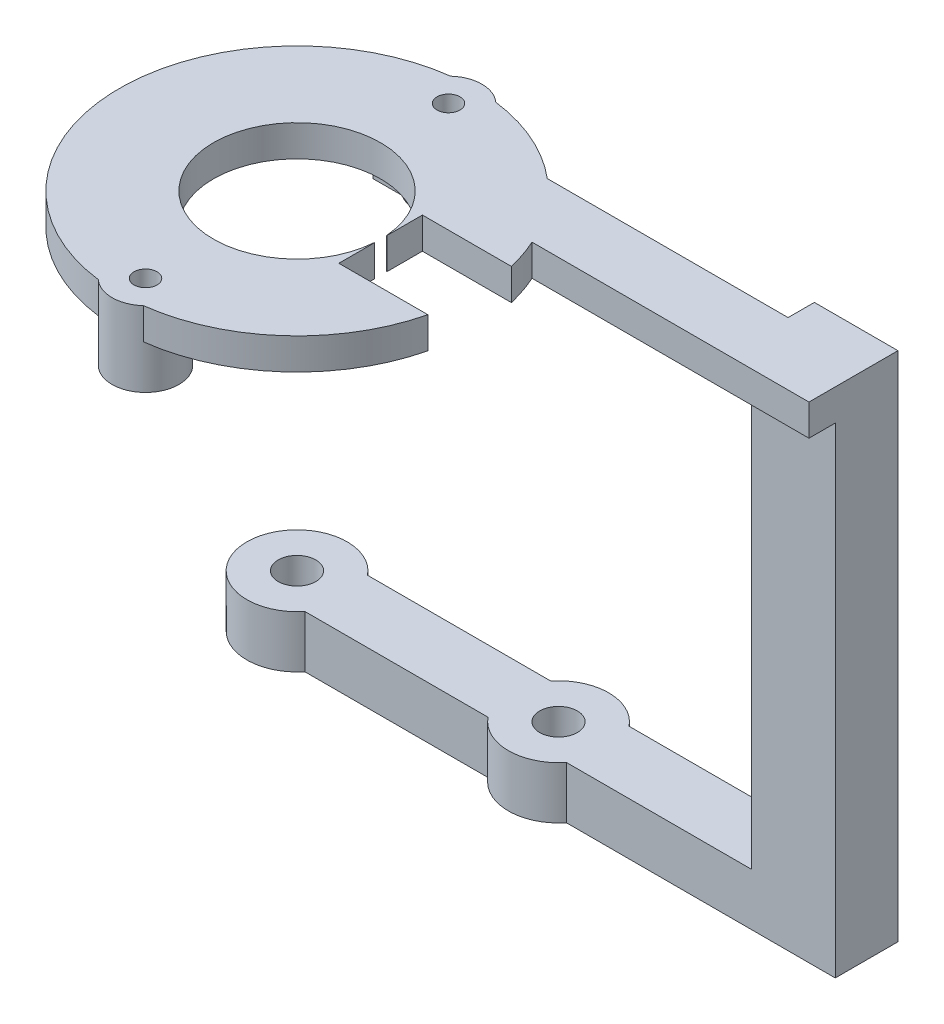
SolidWorks part; units mm, degrees
other "Encoder Carrier Bracket"
ref_plane "Front Plane" through (0, 0, 0) normal (0, 0, 1) x (1, 0, 0)
ref_plane "Top Plane" through (0, 0, 0) normal (0, 1, 0) x (1, 0, 0)
ref_plane "Right Plane" through (0, 0, 0) normal (1, 0, 0) x (0, 0, -1)
sketch3d "Main Profile Sketch datum points"
  point P0 (0, -196, 0)
  point P1 (10, -196, 0)
  point P2 (0, -196, 10)
ref_plane "Main Profile Sketch plane" through (0, -196, 0) normal (0, -1, 0) x (-1, 0, 0)
sketch "Main Profile Sketch" plane through (0, -196, 0) normal (0, -1, 0) x (-1, 0, 0)
  line L0 (-14.9908, 66.2449) -> (8.0547, 66.2449)
  line L1 (-14.9908, 68.7607) -> (-14.9908, 66.2449)
  line L2 (-22.9908, 68.7607) -> (-14.9908, 68.7607)
  line L3 (-22.9908, 68.7607) -> (-22.9908, 60.2449)
  line L4 (-22.9908, 60.2449) -> (3.5172, 60.2449)
  line L5 (2.4865, 57.2449) -> (11.0092, 57.2449)
  line L6 (11.0092, 57.2449) -> (11.0092, 53.2449)
  line L7 (11.0092, 53.2449) -> (11.0092, 49.2449)
  line L8 (2.4865, 49.2449) -> (11.0092, 49.2449)
  arc A0 (19.0092, 35.5449) -> (21.1677, 36.3825) centre (19.0092, 38.7449) ccw
  arc A1 (21.1677, 36.3825) -> (21.1677, 70.1073) centre (19.0092, 53.2449) ccw
  arc A2 (21.1677, 70.1073) -> (16.8507, 70.1073) centre (19.0092, 67.7449) ccw
  arc A3 (16.8507, 70.1073) -> (8.0547, 66.2449) centre (19.0092, 53.2449) ccw
  arc A4 (3.5172, 60.2449) -> (2.4865, 57.2449) centre (19.0092, 53.2449) ccw
  arc A5 (2.4865, 49.2449) -> (16.8507, 36.3825) centre (19.0092, 53.2449) ccw
  arc A6 (16.8507, 36.3825) -> (19.0092, 35.5449) centre (19.0092, 38.7449) ccw
  circle A7 centre (19.0092, 67.7449) radius 1.1
  circle A8 centre (19.0092, 38.7449) radius 1.1
extrude "Main Extrusion" add sketch "Main Profile Sketch" along normal blind 3 separate body
sketch3d "Detail Profile 2 Sketch datum points"
  point P0 (0, -199, 0)
  point P1 (10, -199, 0)
  point P2 (0, -199, 10)
ref_plane "Detail Profile 2 Sketch plane" through (0, -199, 0) normal (0, -1, 0) x (-1, 0, 0)
sketch "Detail Profile 2 Sketch" plane through (0, -199, 0) normal (0, -1, 0) x (-1, 0, 0)
  line L0 (16.0092, 42.9949) -> (22.0092, 42.9949)
  line L1 (16.0092, 42.9949) -> (16.0092, 39.8584)
  line L2 (22.0092, 42.9949) -> (22.0092, 39.8584)
  line L3 (-22.9908, 68.7607) -> (-14.9908, 68.7607)
  line L4 (-22.9908, 68.7607) -> (-22.9908, 62.7607)
  line L5 (-22.9908, 62.7607) -> (-14.9908, 62.7607)
  line L6 (-14.9908, 68.7607) -> (-14.9908, 62.7607)
  line L7 (16.0092, 66.6313) -> (16.0092, 63.4949)
  line L8 (16.0092, 63.4949) -> (22.0092, 63.4949)
  line L9 (22.0092, 66.6313) -> (22.0092, 63.4949)
  arc A0 (16.0092, 39.8584) -> (19.0092, 35.5449) centre (19.0092, 38.7449) ccw
  arc A1 (19.0092, 35.5449) -> (22.0092, 39.8584) centre (19.0092, 38.7449) ccw
  circle A2 centre (19.0092, 38.7449) radius 1.1
  arc A3 (22.0092, 66.6313) -> (16.0092, 66.6313) centre (19.0092, 67.7449) ccw
  circle A4 centre (19.0092, 67.7449) radius 1.1
extrude "Detail Extrusion 2" add sketch "Detail Profile 2 Sketch" along normal blind 0.2
sketch3d "Detail Profile 3 Sketch datum points"
  point P0 (0, -199.2, 0)
  point P1 (10, -199.2, 0)
  point P2 (0, -199.2, 10)
ref_plane "Detail Profile 3 Sketch plane" through (0, -199.2, 0) normal (0, -1, 0) x (-1, 0, 0)
sketch "Detail Profile 3 Sketch" plane through (0, -199.2, 0) normal (0, -1, 0) x (-1, 0, 0)
  line L0 (16.0092, 42.9949) -> (22.0092, 42.9949)
  line L1 (16.0092, 42.9949) -> (16.0092, 39.8584)
  line L2 (22.0092, 42.9949) -> (22.0092, 39.8584)
  line L3 (-22.9908, 68.7607) -> (-14.9908, 68.7607)
  line L4 (-22.9908, 68.7607) -> (-22.9908, 62.7607)
  line L5 (-22.9908, 62.7607) -> (-14.9908, 62.7607)
  line L6 (-14.9908, 68.7607) -> (-14.9908, 62.7607)
  line L7 (16.0092, 66.6313) -> (16.0092, 63.4949)
  line L8 (16.0092, 63.4949) -> (22.0092, 63.4949)
  line L9 (22.0092, 66.6313) -> (22.0092, 63.4949)
  arc A0 (16.0092, 39.8584) -> (19.0092, 35.5449) centre (19.0092, 38.7449) ccw
  arc A1 (19.0092, 35.5449) -> (22.0092, 39.8584) centre (19.0092, 38.7449) ccw
  circle A2 centre (19.0092, 38.7449) radius 1.6
  arc A3 (22.0092, 66.6313) -> (16.0092, 66.6313) centre (19.0092, 67.7449) ccw
  circle A4 centre (19.0092, 67.7449) radius 1.6
extrude "Detail Extrusion 3" add sketch "Detail Profile 3 Sketch" along normal blind 2.4
sketch3d "Detail Profile 4 Sketch datum points"
  point P0 (0, -201.6, 0)
  point P1 (10, -201.6, 0)
  point P2 (0, -201.6, 10)
ref_plane "Detail Profile 4 Sketch plane" through (0, -201.6, 0) normal (0, -1, 0) x (-1, 0, 0)
sketch "Detail Profile 4 Sketch" plane through (0, -201.6, 0) normal (0, -1, 0) x (-1, 0, 0)
  line L0 (-22.9908, 68.7607) -> (-14.9908, 68.7607)
  line L1 (-22.9908, 68.7607) -> (-22.9908, 62.7607)
  line L2 (-22.9908, 62.7607) -> (-14.9908, 62.7607)
  line L3 (-14.9908, 68.7607) -> (-14.9908, 62.7607)
  circle A0 centre (19.0092, 38.7449) radius 3.2
  circle A1 centre (19.0092, 38.7449) radius 1.6
  circle A2 centre (19.0092, 67.7449) radius 3.2
  circle A3 centre (19.0092, 67.7449) radius 1.6
extrude "Detail Extrusion 4" add sketch "Detail Profile 4 Sketch" along normal blind 1.6
sketch3d "Detail Profile 5 Sketch datum points"
  point P0 (0, -203.2, 0)
  point P1 (10, -203.2, 0)
  point P2 (0, -203.2, 10)
ref_plane "Detail Profile 5 Sketch plane" through (0, -203.2, 0) normal (0, -1, 0) x (-1, 0, 0)
sketch "Detail Profile 5 Sketch" plane through (0, -203.2, 0) normal (0, -1, 0) x (-1, 0, 0)
  line L0 (-22.9908, 68.7607) -> (-14.9908, 68.7607)
  line L1 (-22.9908, 68.7607) -> (-22.9908, 62.7607)
  line L2 (-22.9908, 62.7607) -> (-14.9908, 62.7607)
  line L3 (-14.9908, 68.7607) -> (-14.9908, 62.7607)
extrude "Detail Extrusion 5" add sketch "Detail Profile 5 Sketch" along normal blind 36.8
sketch3d "Detail Profile 6 Sketch datum points"
  point P0 (0, -240, 0)
  point P1 (10, -240, 0)
  point P2 (0, -240, 10)
ref_plane "Detail Profile 6 Sketch plane" through (0, -240, 0) normal (0, -1, 0) x (-1, 0, 0)
sketch "Detail Profile 6 Sketch" plane through (0, -240, 0) normal (0, -1, 0) x (-1, 0, 0)
  line L0 (-22.9908, 62.7607) -> (2.7464, 62.7607)
  line L1 (10.2404, 62.7607) -> (27.778, 62.7607)
  line L2 (10.2404, 68.7607) -> (27.778, 68.7607)
  line L3 (-22.9908, 68.7607) -> (2.7464, 68.7607)
  line L4 (-22.9908, 68.7607) -> (-22.9908, 62.7607)
  arc A0 (2.7464, 62.7607) -> (10.2404, 62.7607) centre (6.4934, 65.7607) ccw
  arc A1 (27.778, 62.7607) -> (27.778, 68.7607) centre (31.525, 65.7607) ccw
  arc A2 (10.2404, 68.7607) -> (2.7464, 68.7607) centre (6.4934, 65.7607) ccw
  circle A3 centre (31.525, 65.7607) radius 1.8
  circle A4 centre (6.4934, 65.7607) radius 1.8
extrude "Detail Extrusion 6" add sketch "Detail Profile 6 Sketch" along normal blind 5
sketch3d "Centre Bore Relief Slot Sketch datum points"
  point P0 (-19.0092, -199.1, -53.2449)
  point P1 (-9.0092, -199.1, -53.2449)
  point P2 (-19.0092, -199.1, -63.2449)
ref_plane "Centre Bore Relief Slot Sketch plane" through (0, -199.1, 0) normal (0, 1, 0) x (1, 0, 0)
sketch "Centre Bore Relief Slot Sketch" plane through (0, -199.1, 0) normal (0, 1, 0) x (1, 0, 0)
  line L0 (-19.0092, 53.8449) -> (-10.0092, 53.8449)
  line L1 (-10.0092, 53.8449) -> (-10.0092, 52.6449)
  line L2 (-10.0092, 52.6449) -> (-19.0092, 52.6449)
  line L3 (-19.0092, 52.6449) -> (-19.0092, 53.8449)
extrude "Centre Bore Relief Slot" cut sketch "Centre Bore Relief Slot Sketch" along normal blind 3.2
sketch3d "Encoder Centre Opening profile datum points"
  point P0 (-19.0092, -199.1, -53.2449)
  point P1 (-9.0092, -199.1, -53.2449)
  point P2 (-19.0092, -199.1, -63.2449)
ref_plane "Encoder Centre Opening profile plane" through (0, -199.1, 0) normal (0, 1, 0) x (1, 0, 0)
sketch "Encoder Centre Opening profile" plane through (0, -199.1, 0) normal (0, 1, 0) x (1, 0, 0)
  circle A0 centre (-19.0092, 53.2449) radius 8
extrude "Encoder Centre Opening" cut sketch "Encoder Centre Opening profile" along normal blind 3.2
